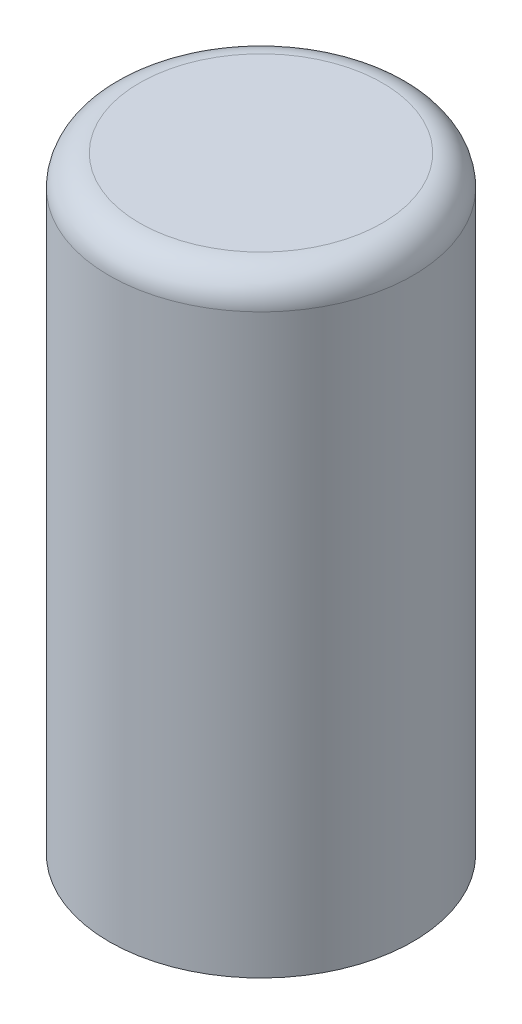
SolidWorks part; units mm, degrees
ref_plane "Front Plane" through (0, 0, 0) normal (0, 0, 1) x (1, 0, 0)
ref_plane "Top Plane" through (0, 0, 0) normal (0, 1, 0) x (1, 0, 0)
ref_plane "Right Plane" through (0, 0, 0) normal (1, 0, 0) x (0, 0, -1)
sketch "Sketch1" plane through (0, 0, 0) normal (0, 1, 0) x (1, 0, 0)
  circle A0 centre (0, 0) radius 5
  dimension "D1" = 10
extrude "Boss-Extrude1" add sketch "Sketch1" along normal blind 20
fillet "Fillet1" radius 1 1 edges at (0, 20, 5)
sketch "Sketch2" plane through (0, 0, 0) normal (0, -1, 0) x (-1, 0, 0)
  line L0 (1.44, -2.6887) -> (1.44, 2.6887)
  circle A0 centre (0, 0) radius 3.05
  dimension "D1" = 6.1
  dimension "D2" = 4.49
extrude "Cut-Extrude1" cut sketch "Sketch2" against normal blind 15 contours L0 A0
sketch "Sketch4" plane through (0, 0, 0) normal (0, -1, 0) x (-1, 0, 0)
  circle A0 centre (0, 0) radius 3.05
extrude "Cut-Extrude2" cut sketch "Sketch4" against normal blind 3
